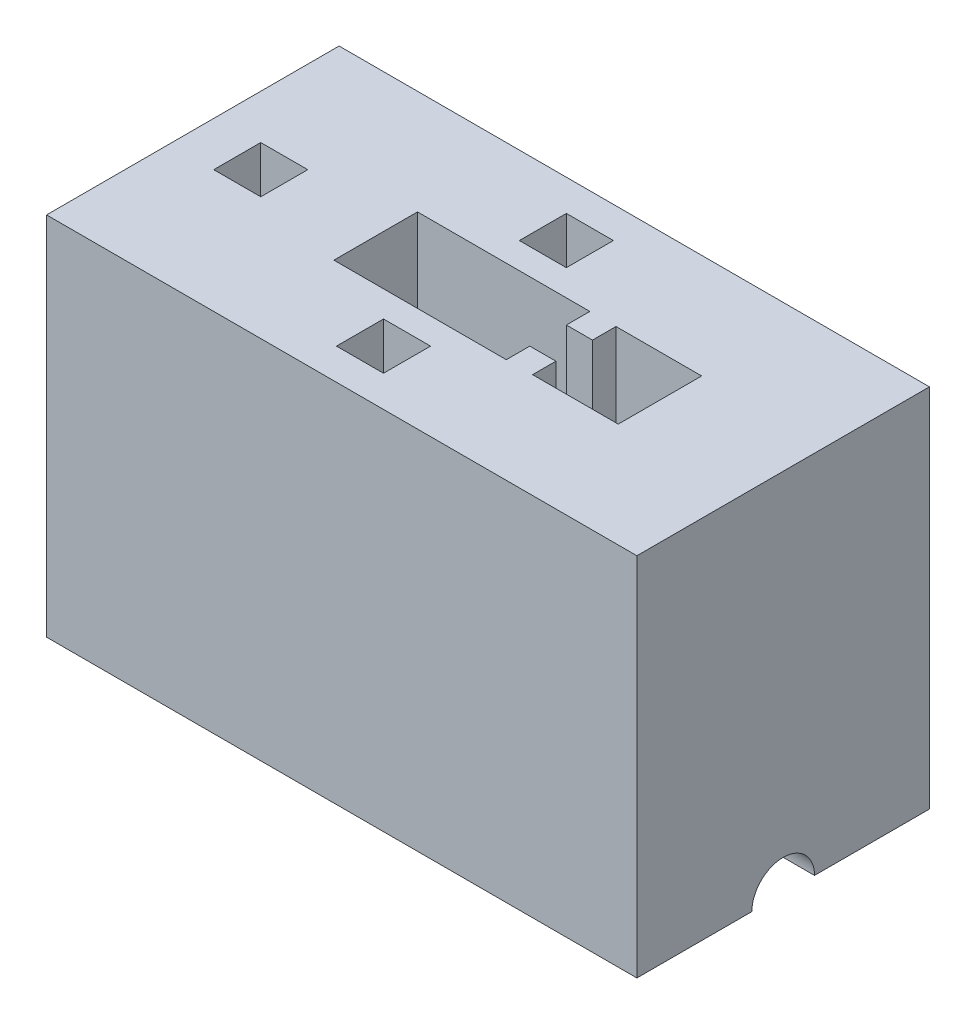
SolidWorks part; units mm, degrees
ref_plane "Front Plane" through (0, 0, 0) normal (0, 0, 1) x (1, 0, 0)
ref_plane "Top Plane" through (0, 0, 0) normal (0, 1, 0) x (1, 0, 0)
ref_plane "Right Plane" through (0, 0, 0) normal (1, 0, 0) x (0, 0, -1)
sketch "Sketch1" plane through (0, 0, 0) normal (0, 1, 0) x (1, 0, 0)
  line L1 (-120.7765, 11.7534) -> (22.7335, 11.7534)
  line L2 (-120.7765, 11.7534) -> (-120.7765, -110.1666)
  line L3 (-120.7765, -110.1666) -> (22.7335, -110.1666)
  line L4 (22.7335, 11.7534) -> (22.7335, -110.1666)
  dimension "D1" = 143.51
  dimension "D2" = 121.92
extrude "Big Block" add sketch "Sketch1" along normal blind 88.9
sketch "Sketch2" plane through (0, 88.9, 0) normal (0, 1, 0) x (1, 0, 0)
  line L0 (-76.3265, -39.0466) -> (-34.4165, -39.0466)
  line L5 (-76.3265, -39.0466) -> (-76.3265, -59.3666)
  line L6 (-76.3265, -59.3666) -> (-34.4165, -59.3666)
  line L8 (22.7335, 11.7534) -> (-120.7765, 11.7534) construction
  line L10 (-34.4165, -39.0466) -> (-34.4165, -44.7616)
  line L11 (-34.4165, -44.7616) -> (-19.1765, -44.7616)
  line L12 (-19.1765, -44.7616) -> (-19.1765, -53.6516)
  line L13 (-19.1765, -53.6516) -> (-34.4165, -53.6516)
  line L14 (-34.4165, -53.6516) -> (-34.4165, -59.3666)
  point P8 (-19.1765, -49.2066)
  dimension "D1" = 20.32
  dimension "D2" = 41.91
  dimension "D3" = 50.8
  dimension "D4" = 15.24
  dimension "D5" = 8.89
  dimension "D6" = 10.16
extrude "Servo Cutout" cut sketch "Sketch2" against normal blind 25.654
sketch "Sketch3" plane through (0, 0, 0) normal (0, -1, 0) x (-1, 0, 0)
  line L0 (-22.7335, 11.7534) -> (120.7765, 11.7534) construction
  line L1 (109.9815, -77.1466) -> (-11.9385, -77.1466)
  line L2 (109.9815, -77.1466) -> (109.9815, -21.2666)
  line L3 (109.9815, -21.2666) -> (-11.9385, -21.2666)
  line L4 (-11.9385, -77.1466) -> (-11.9385, -21.2666)
  line L6 (-22.7335, -110.1666) -> (-22.7335, 11.7534) construction
  line L8 (120.7765, 11.7534) -> (120.7765, -110.1666) construction
  dimension "D1" = 121.92
  dimension "D2" = 55.88
  dimension "D3" = 33.02
  dimension "D4" = 10.795
  dimension "D5" = 10.795
extrude "Cut-Extrude2" cut sketch "Sketch3" against normal blind 50.8
sketch "Sketch4" plane through (48.1335, 88.9, 0) normal (0, -1, 0) x (0, 0, 1)
  line L1 (39.7487, 143.256) -> (60.0687, 143.256)
  line L2 (39.7487, 143.256) -> (39.7487, 153.416)
  line L3 (39.7487, 153.416) -> (60.0687, 153.416)
  line L4 (60.0687, 143.256) -> (60.0687, 153.416)
  line L6 (-11.7534, 168.91) -> (110.1666, 168.91) construction
  dimension "D1" = 10.16
  dimension "D2" = 25.654
sketch "Sketch5" plane through (0, 88.9, 0) normal (0, 1, 0) x (1, 0, 0)
  line L1 (-28.0665, -39.0466) -> (-7.2436, -39.0466)
  line L2 (-28.0665, -39.0466) -> (-28.0665, -59.3247)
  line L3 (-28.0665, -59.3247) -> (-7.2436, -59.3247)
  line L4 (-7.2436, -39.0466) -> (-7.2436, -59.3247)
sketch "Sketch6" plane through (0, 50.8, 0) normal (0, -1, 0) x (1, 0, 0)
  line L0 (-28.0665, 59.3247) -> (-7.2436, 59.3247) construction
  line L1 (-28.0665, 39.0466) -> (-28.0665, 59.3247) construction
  line L2 (-28.0665, 39.0466) -> (-7.2436, 39.0466) construction
  line L3 (-7.2436, 39.0466) -> (-7.2436, 59.3247) construction
  line L4 (-28.0665, 59.3247) -> (-7.2436, 59.3247)
  line L5 (-28.0665, 39.0466) -> (-28.0665, 59.3247)
  line L6 (-28.0665, 39.0466) -> (-7.2436, 39.0466)
  line L7 (-7.2436, 39.0466) -> (-7.2436, 59.3247)
extrude "Cut-Extrude18" cut sketch "Sketch6" along normal through all and the other way blind 48.26
sketch "Sketch7" plane through (0, 88.9, 0) normal (0, 1, 0) x (1, 0, 0)
  line L0 (-34.4165, -39.0466) -> (-76.3265, -39.0466) construction
  line L1 (-9.0165, -46.6666) -> (-3.9365, -46.6666)
  line L2 (-9.0165, -46.6666) -> (-9.0165, -51.7466)
  line L3 (-9.0165, -51.7466) -> (-3.9365, -51.7466)
  line L4 (-3.9365, -46.6666) -> (-3.9365, -51.7466)
  line L5 (-34.4165, -59.3666) -> (-34.4165, -53.6516) construction
  point P4 (-9.0165, -49.2066)
  dimension "D1" = 5.08
  dimension "D2" = 5.08
  dimension "D3" = 10.16
  dimension "D4" = 25.4
sketch "Sketch9" plane through (0, 88.9, 0) normal (0, 1, 0) x (1, 0, 0)
  line L0 (-109.9815, -77.1466) -> (-109.9815, -21.2666) construction
  line L1 (-109.9815, -43.4916) -> (-98.5515, -43.4916)
  line L2 (-109.9815, -43.4916) -> (-109.9815, -54.9216)
  line L3 (-109.9815, -54.9216) -> (-98.5515, -54.9216)
  line L4 (-98.5515, -43.4916) -> (-98.5515, -54.9216)
  line L5 (-34.4165, -39.0466) -> (-76.3265, -39.0466) construction
  dimension "D1" = 11.43
  dimension "D2" = 11.43
  dimension "D3" = 0
  dimension "D4" = 4.445
sketch "Sketch10" plane through (0, 88.9, 0) normal (0, 1, 0) x (1, 0, 0)
  line L1 (-57.9115, -21.2666) -> (-46.4815, -21.2666)
  line L2 (-57.9115, -21.2666) -> (-57.9115, -32.6966)
  line L3 (-57.9115, -32.6966) -> (-46.4815, -32.6966)
  line L4 (-46.4815, -21.2666) -> (-46.4815, -32.6966)
  line L5 (-109.9815, -21.2666) -> (11.9385, -21.2666) construction
  line L8 (-76.3265, -39.0466) -> (-76.3265, -59.3666) construction
  dimension "D1" = 11.43
  dimension "D2" = 0
  dimension "D4" = 18.415
sketch "Sketch11" plane through (0, 88.9, 0) normal (0, 1, 0) x (1, 0, 0)
  line L0 (11.9385, -77.1466) -> (-109.9815, -77.1466) construction
  line L1 (-57.9115, -65.7166) -> (-46.4815, -65.7166)
  line L2 (-57.9115, -65.7166) -> (-57.9115, -77.1466)
  line L3 (-57.9115, -77.1466) -> (-46.4815, -77.1466)
  line L4 (-46.4815, -65.7166) -> (-46.4815, -77.1466)
  line L8 (-76.3265, -39.0466) -> (-76.3265, -59.3666) construction
  dimension "D1" = 11.43
  dimension "D2" = 11.43
  dimension "D3" = 0
  dimension "D4" = 18.415
extrude "Cut-Extrude19" cut sketch "Sketch10" against normal through all
extrude "Cut-Extrude20" cut sketch "Sketch11" against normal through all
extrude "Cut-Extrude22" cut sketch "Sketch9" against normal through all
sketch "Sketch12" plane through (0, 0, 0) normal (0, -1, 0) x (-1, 0, 0)
  line L0 (-22.7335, -110.1666) -> (-22.7335, 11.7534) construction
  line L1 (120.7765, -110.1666) -> (-22.7335, -110.1666)
  line L2 (120.7765, -110.1666) -> (120.7765, -84.7666)
  line L3 (120.7765, -84.7666) -> (-22.7335, -84.7666)
  line L4 (-22.7335, -110.1666) -> (-22.7335, -84.7666)
  line L5 (120.7765, -13.6466) -> (-22.7335, -13.6466)
  line L6 (120.7765, -13.6466) -> (120.7765, 11.7534)
  line L7 (120.7765, 11.7534) -> (-22.7335, 11.7534)
  line L8 (-22.7335, -13.6466) -> (-22.7335, 11.7534)
  dimension "D1" = 25.4
  dimension "D2" = 25.4
  dimension "D3" = 143.51
extrude "removesides" cut sketch "Sketch12" against normal through all
sketch "Sketch13" plane through (-120.7765, 0, 0) normal (-1, 0, 0) x (0, 0, 1)
  line L0 (13.6466, 0) -> (84.7666, 0) construction
  line L1 (41.5866, 0) -> (56.8266, 0)
  arc A0 (56.8266, 0) -> (41.5866, 0) centre (49.2066, 0) ccw
  dimension "D1" = 15.24
extrude "Cut-Extrude23" cut sketch "Sketch13" against normal through all both and the other way through all
